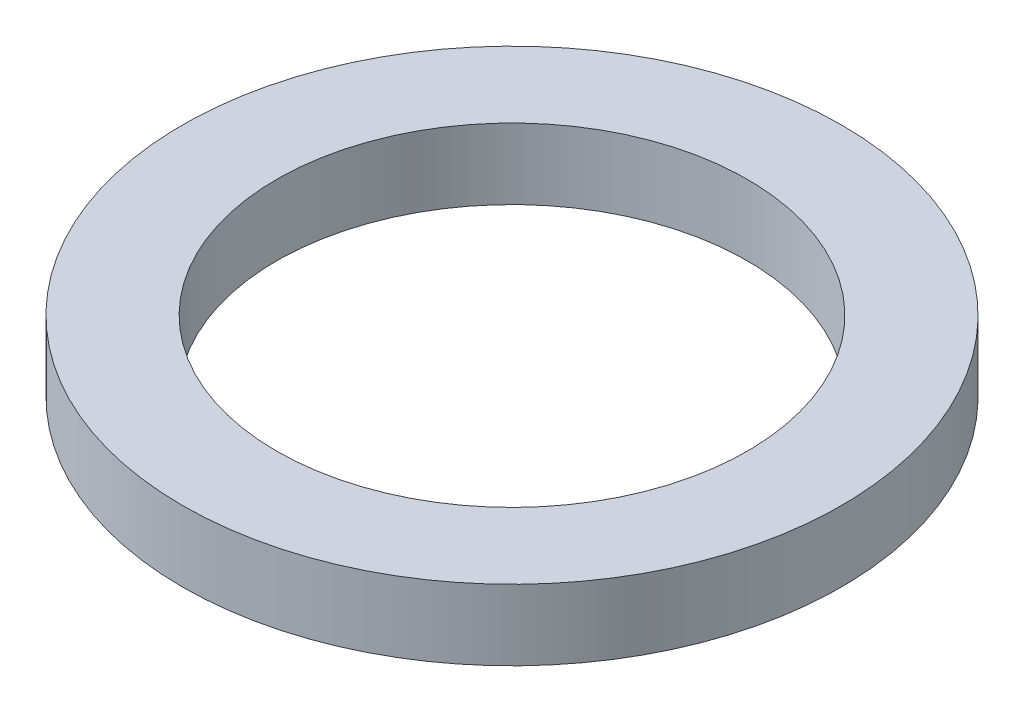
SolidWorks part; units mm, degrees
ref_plane "Front Plane" through (0, 0, 0) normal (0, 0, 1) x (1, 0, 0)
ref_plane "Top Plane" through (0, 0, 0) normal (0, 1, 0) x (1, 0, 0)
ref_plane "Right Plane" through (0, 0, 0) normal (1, 0, 0) x (0, 0, -1)
sketch "Sketch1" plane through (0, 0, 0) normal (0, 1, 0) x (1, 0, 0)
  circle A0 centre (0, 0) radius 10
  circle A1 centre (0, 0) radius 14
  dimension "D1" = 20
  dimension "D2" = 4
extrude "Boss-Extrude1" add sketch "Sketch1" along normal blind 3
